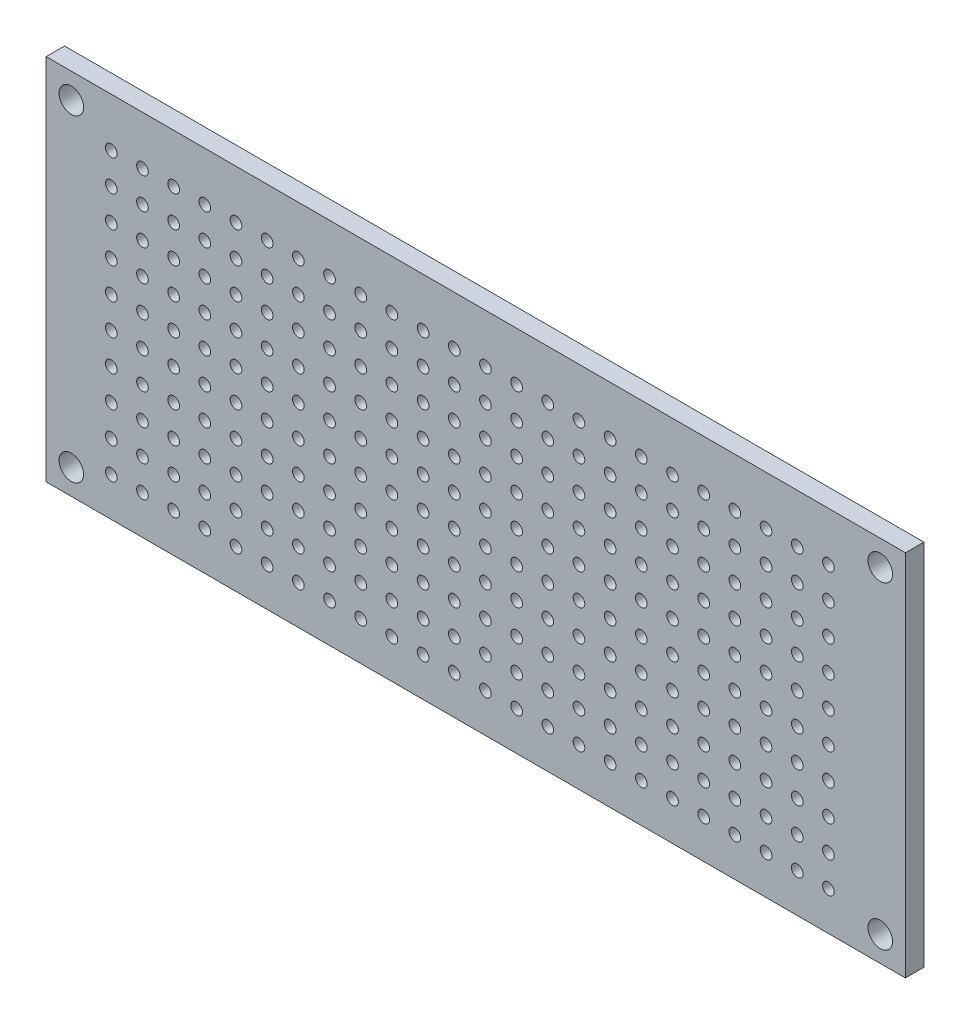
SolidWorks part; units mm, degrees
ref_plane "Ebene vorne" through (0, 0, 0) normal (0, 0, 1) x (1, 0, 0)
ref_plane "Ebene oben" through (0, 0, 0) normal (0, 1, 0) x (1, 0, 0)
ref_plane "Ebene rechts" through (0, 0, 0) normal (1, 0, 0) x (0, 0, -1)
sketch "Skizze1" plane through (0, 0, 0) normal (0, 0, 1) x (1, 0, 0)
  line L1 (0, 0) -> (70, 0)
  line L2 (0, 0) -> (0, 30)
  line L3 (0, 30) -> (70, 30)
  line L4 (70, 0) -> (70, 30)
  circle A0 centre (67.95, 27.95) radius 1
  circle A1 centre (67.95, 2.05) radius 1
  circle A2 centre (2.05, 2.05) radius 1
  circle A3 centre (2.05, 27.95) radius 1
  circle A4 centre (63.725, 26.025) radius 0.475
  circle A5 centre (61.185, 26.025) radius 0.475
  circle A6 centre (58.645, 26.025) radius 0.475
  circle A7 centre (56.105, 26.025) radius 0.475
  circle A8 centre (53.565, 26.025) radius 0.475
  circle A9 centre (51.025, 26.025) radius 0.475
  circle A10 centre (48.485, 26.025) radius 0.475
  circle A11 centre (45.945, 26.025) radius 0.475
  circle A12 centre (43.405, 26.025) radius 0.475
  circle A13 centre (40.865, 26.025) radius 0.475
  circle A14 centre (38.325, 26.025) radius 0.475
  circle A15 centre (35.785, 26.025) radius 0.475
  circle A16 centre (33.245, 26.025) radius 0.475
  circle A17 centre (30.705, 26.025) radius 0.475
  circle A18 centre (28.165, 26.025) radius 0.475
  circle A19 centre (25.625, 26.025) radius 0.475
  circle A20 centre (23.085, 26.025) radius 0.475
  circle A21 centre (20.545, 26.025) radius 0.475
  circle A22 centre (18.005, 26.025) radius 0.475
  circle A23 centre (15.465, 26.025) radius 0.475
  circle A24 centre (12.925, 26.025) radius 0.475
  circle A25 centre (10.385, 26.025) radius 0.475
  circle A26 centre (7.845, 26.025) radius 0.475
  circle A27 centre (5.305, 26.025) radius 0.475
  circle A28 centre (61.185, 23.485) radius 0.475
  circle A29 centre (58.645, 23.485) radius 0.475
  circle A30 centre (56.105, 23.485) radius 0.475
  circle A31 centre (53.565, 23.485) radius 0.475
  circle A32 centre (51.025, 23.485) radius 0.475
  circle A33 centre (48.485, 23.485) radius 0.475
  circle A34 centre (45.945, 23.485) radius 0.475
  circle A35 centre (43.405, 23.485) radius 0.475
  circle A36 centre (40.865, 23.485) radius 0.475
  circle A37 centre (38.325, 23.485) radius 0.475
  circle A38 centre (35.785, 23.485) radius 0.475
  circle A39 centre (33.245, 23.485) radius 0.475
  circle A40 centre (30.705, 23.485) radius 0.475
  circle A41 centre (28.165, 23.485) radius 0.475
  circle A42 centre (25.625, 23.485) radius 0.475
  circle A43 centre (23.085, 23.485) radius 0.475
  circle A44 centre (20.545, 23.485) radius 0.475
  circle A45 centre (18.005, 23.485) radius 0.475
  circle A46 centre (15.465, 23.485) radius 0.475
  circle A47 centre (12.925, 23.485) radius 0.475
  circle A48 centre (10.385, 23.485) radius 0.475
  circle A49 centre (7.845, 23.485) radius 0.475
  circle A50 centre (5.305, 23.485) radius 0.475
  circle A51 centre (61.185, 20.945) radius 0.475
  circle A52 centre (58.645, 20.945) radius 0.475
  circle A53 centre (56.105, 20.945) radius 0.475
  circle A54 centre (53.565, 20.945) radius 0.475
  circle A55 centre (51.025, 20.945) radius 0.475
  circle A56 centre (48.485, 20.945) radius 0.475
  circle A57 centre (45.945, 20.945) radius 0.475
  circle A58 centre (43.405, 20.945) radius 0.475
  circle A59 centre (40.865, 20.945) radius 0.475
  circle A60 centre (38.325, 20.945) radius 0.475
  circle A61 centre (35.785, 20.945) radius 0.475
  circle A62 centre (33.245, 20.945) radius 0.475
  circle A63 centre (30.705, 20.945) radius 0.475
  circle A64 centre (28.165, 20.945) radius 0.475
  circle A65 centre (25.625, 20.945) radius 0.475
  circle A66 centre (23.085, 20.945) radius 0.475
  circle A67 centre (20.545, 20.945) radius 0.475
  circle A68 centre (18.005, 20.945) radius 0.475
  circle A69 centre (15.465, 20.945) radius 0.475
  circle A70 centre (12.925, 20.945) radius 0.475
  circle A71 centre (10.385, 20.945) radius 0.475
  circle A72 centre (7.845, 20.945) radius 0.475
  circle A73 centre (5.305, 20.945) radius 0.475
  circle A74 centre (61.185, 18.405) radius 0.475
  circle A75 centre (58.645, 18.405) radius 0.475
  circle A76 centre (56.105, 18.405) radius 0.475
  circle A77 centre (53.565, 18.405) radius 0.475
  circle A78 centre (51.025, 18.405) radius 0.475
  circle A79 centre (48.485, 18.405) radius 0.475
  circle A80 centre (45.945, 18.405) radius 0.475
  circle A81 centre (43.405, 18.405) radius 0.475
  circle A82 centre (40.865, 18.405) radius 0.475
  circle A83 centre (38.325, 18.405) radius 0.475
  circle A84 centre (35.785, 18.405) radius 0.475
  circle A85 centre (33.245, 18.405) radius 0.475
  circle A86 centre (30.705, 18.405) radius 0.475
  circle A87 centre (28.165, 18.405) radius 0.475
  circle A88 centre (25.625, 18.405) radius 0.475
  circle A89 centre (23.085, 18.405) radius 0.475
  circle A90 centre (20.545, 18.405) radius 0.475
  circle A91 centre (18.005, 18.405) radius 0.475
  circle A92 centre (15.465, 18.405) radius 0.475
  circle A93 centre (12.925, 18.405) radius 0.475
  circle A94 centre (10.385, 18.405) radius 0.475
  circle A95 centre (7.845, 18.405) radius 0.475
  circle A96 centre (5.305, 18.405) radius 0.475
  circle A97 centre (61.185, 15.865) radius 0.475
  circle A98 centre (58.645, 15.865) radius 0.475
  circle A99 centre (56.105, 15.865) radius 0.475
  circle A100 centre (53.565, 15.865) radius 0.475
  circle A101 centre (51.025, 15.865) radius 0.475
  circle A102 centre (48.485, 15.865) radius 0.475
  circle A103 centre (45.945, 15.865) radius 0.475
  circle A104 centre (43.405, 15.865) radius 0.475
  circle A105 centre (40.865, 15.865) radius 0.475
  circle A106 centre (38.325, 15.865) radius 0.475
  circle A107 centre (35.785, 15.865) radius 0.475
  circle A108 centre (33.245, 15.865) radius 0.475
  circle A109 centre (30.705, 15.865) radius 0.475
  circle A110 centre (28.165, 15.865) radius 0.475
  circle A111 centre (25.625, 15.865) radius 0.475
  circle A112 centre (23.085, 15.865) radius 0.475
  circle A113 centre (20.545, 15.865) radius 0.475
  circle A114 centre (18.005, 15.865) radius 0.475
  circle A115 centre (15.465, 15.865) radius 0.475
  circle A116 centre (12.925, 15.865) radius 0.475
  circle A117 centre (10.385, 15.865) radius 0.475
  circle A118 centre (7.845, 15.865) radius 0.475
  circle A119 centre (5.305, 15.865) radius 0.475
  circle A120 centre (61.185, 13.325) radius 0.475
  circle A121 centre (58.645, 13.325) radius 0.475
  circle A122 centre (56.105, 13.325) radius 0.475
  circle A123 centre (53.565, 13.325) radius 0.475
  circle A124 centre (51.025, 13.325) radius 0.475
  circle A125 centre (48.485, 13.325) radius 0.475
  circle A126 centre (45.945, 13.325) radius 0.475
  circle A127 centre (43.405, 13.325) radius 0.475
  circle A128 centre (40.865, 13.325) radius 0.475
  circle A129 centre (38.325, 13.325) radius 0.475
  circle A130 centre (35.785, 13.325) radius 0.475
  circle A131 centre (33.245, 13.325) radius 0.475
  circle A132 centre (30.705, 13.325) radius 0.475
  circle A133 centre (28.165, 13.325) radius 0.475
  circle A134 centre (25.625, 13.325) radius 0.475
  circle A135 centre (23.085, 13.325) radius 0.475
  circle A136 centre (20.545, 13.325) radius 0.475
  circle A137 centre (18.005, 13.325) radius 0.475
  circle A138 centre (15.465, 13.325) radius 0.475
  circle A139 centre (12.925, 13.325) radius 0.475
  circle A140 centre (10.385, 13.325) radius 0.475
  circle A141 centre (7.845, 13.325) radius 0.475
  circle A142 centre (5.305, 13.325) radius 0.475
  circle A143 centre (61.185, 10.785) radius 0.475
  circle A144 centre (58.645, 10.785) radius 0.475
  circle A145 centre (56.105, 10.785) radius 0.475
  circle A146 centre (53.565, 10.785) radius 0.475
  circle A147 centre (51.025, 10.785) radius 0.475
  circle A148 centre (48.485, 10.785) radius 0.475
  circle A149 centre (45.945, 10.785) radius 0.475
  circle A150 centre (43.405, 10.785) radius 0.475
  circle A151 centre (40.865, 10.785) radius 0.475
  circle A152 centre (38.325, 10.785) radius 0.475
  circle A153 centre (35.785, 10.785) radius 0.475
  circle A154 centre (33.245, 10.785) radius 0.475
  circle A155 centre (30.705, 10.785) radius 0.475
  circle A156 centre (28.165, 10.785) radius 0.475
  circle A157 centre (25.625, 10.785) radius 0.475
  circle A158 centre (23.085, 10.785) radius 0.475
  circle A159 centre (20.545, 10.785) radius 0.475
  circle A160 centre (18.005, 10.785) radius 0.475
  circle A161 centre (15.465, 10.785) radius 0.475
  circle A162 centre (12.925, 10.785) radius 0.475
  circle A163 centre (10.385, 10.785) radius 0.475
  circle A164 centre (7.845, 10.785) radius 0.475
  circle A165 centre (5.305, 10.785) radius 0.475
  circle A166 centre (61.185, 8.245) radius 0.475
  circle A167 centre (58.645, 8.245) radius 0.475
  circle A168 centre (56.105, 8.245) radius 0.475
  circle A169 centre (53.565, 8.245) radius 0.475
  circle A170 centre (51.025, 8.245) radius 0.475
  circle A171 centre (48.485, 8.245) radius 0.475
  circle A172 centre (45.945, 8.245) radius 0.475
  circle A173 centre (43.405, 8.245) radius 0.475
  circle A174 centre (40.865, 8.245) radius 0.475
  circle A175 centre (38.325, 8.245) radius 0.475
  circle A176 centre (35.785, 8.245) radius 0.475
  circle A177 centre (33.245, 8.245) radius 0.475
  circle A178 centre (30.705, 8.245) radius 0.475
  circle A179 centre (28.165, 8.245) radius 0.475
  circle A180 centre (25.625, 8.245) radius 0.475
  circle A181 centre (23.085, 8.245) radius 0.475
  circle A182 centre (20.545, 8.245) radius 0.475
  circle A183 centre (18.005, 8.245) radius 0.475
  circle A184 centre (15.465, 8.245) radius 0.475
  circle A185 centre (12.925, 8.245) radius 0.475
  circle A186 centre (10.385, 8.245) radius 0.475
  circle A187 centre (7.845, 8.245) radius 0.475
  circle A188 centre (5.305, 8.245) radius 0.475
  circle A189 centre (61.185, 5.705) radius 0.475
  circle A190 centre (58.645, 5.705) radius 0.475
  circle A191 centre (56.105, 5.705) radius 0.475
  circle A192 centre (53.565, 5.705) radius 0.475
  circle A193 centre (51.025, 5.705) radius 0.475
  circle A194 centre (48.485, 5.705) radius 0.475
  circle A195 centre (45.945, 5.705) radius 0.475
  circle A196 centre (43.405, 5.705) radius 0.475
  circle A197 centre (40.865, 5.705) radius 0.475
  circle A198 centre (38.325, 5.705) radius 0.475
  circle A199 centre (35.785, 5.705) radius 0.475
  circle A200 centre (33.245, 5.705) radius 0.475
  circle A201 centre (30.705, 5.705) radius 0.475
  circle A202 centre (28.165, 5.705) radius 0.475
  circle A203 centre (25.625, 5.705) radius 0.475
  circle A204 centre (23.085, 5.705) radius 0.475
  circle A205 centre (20.545, 5.705) radius 0.475
  circle A206 centre (18.005, 5.705) radius 0.475
  circle A207 centre (15.465, 5.705) radius 0.475
  circle A208 centre (12.925, 5.705) radius 0.475
  circle A209 centre (10.385, 5.705) radius 0.475
  circle A210 centre (7.845, 5.705) radius 0.475
  circle A211 centre (5.305, 5.705) radius 0.475
  circle A212 centre (61.185, 3.165) radius 0.475
  circle A213 centre (58.645, 3.165) radius 0.475
  circle A214 centre (56.105, 3.165) radius 0.475
  circle A215 centre (53.565, 3.165) radius 0.475
  circle A216 centre (51.025, 3.165) radius 0.475
  circle A217 centre (48.485, 3.165) radius 0.475
  circle A218 centre (45.945, 3.165) radius 0.475
  circle A219 centre (43.405, 3.165) radius 0.475
  circle A220 centre (40.865, 3.165) radius 0.475
  circle A221 centre (38.325, 3.165) radius 0.475
  circle A222 centre (35.785, 3.165) radius 0.475
  circle A223 centre (33.245, 3.165) radius 0.475
  circle A224 centre (30.705, 3.165) radius 0.475
  circle A225 centre (28.165, 3.165) radius 0.475
  circle A226 centre (25.625, 3.165) radius 0.475
  circle A227 centre (23.085, 3.165) radius 0.475
  circle A228 centre (20.545, 3.165) radius 0.475
  circle A229 centre (18.005, 3.165) radius 0.475
  circle A230 centre (15.465, 3.165) radius 0.475
  circle A231 centre (12.925, 3.165) radius 0.475
  circle A232 centre (10.385, 3.165) radius 0.475
  circle A233 centre (7.845, 3.165) radius 0.475
  circle A234 centre (5.305, 3.165) radius 0.475
  circle A235 centre (63.725, 23.485) radius 0.475
  circle A236 centre (63.725, 20.945) radius 0.475
  circle A237 centre (63.725, 18.405) radius 0.475
  circle A238 centre (63.725, 15.865) radius 0.475
  circle A239 centre (63.725, 13.325) radius 0.475
  circle A240 centre (63.725, 10.785) radius 0.475
  circle A241 centre (63.725, 8.245) radius 0.475
  circle A242 centre (63.725, 5.705) radius 0.475
  circle A243 centre (63.725, 3.165) radius 0.475
  dimension "D3" = 2
  dimension "D8" = 0.95
  dimension "D1" = 70
  dimension "D2" = 30
  dimension "D4" = 65.9
  dimension "D5" = 25.9
  dimension "D6" = 2.05
  dimension "D7" = 2.05
  dimension "D9" = 3.975
  dimension "D10" = 6.275
  dimension "D11" = 24
  dimension "D12" = 10
extrude "Aufsatz-Linear austragen1" add sketch "Skizze1" along normal blind 1.5
equation "\"D6@Skizze1\"=(\"D2@Skizze1\"-\"D5@Skizze1\")/2"
equation "\"D7@Skizze1\"=(\"D1@Skizze1\"-\"D4@Skizze1\")/2"
